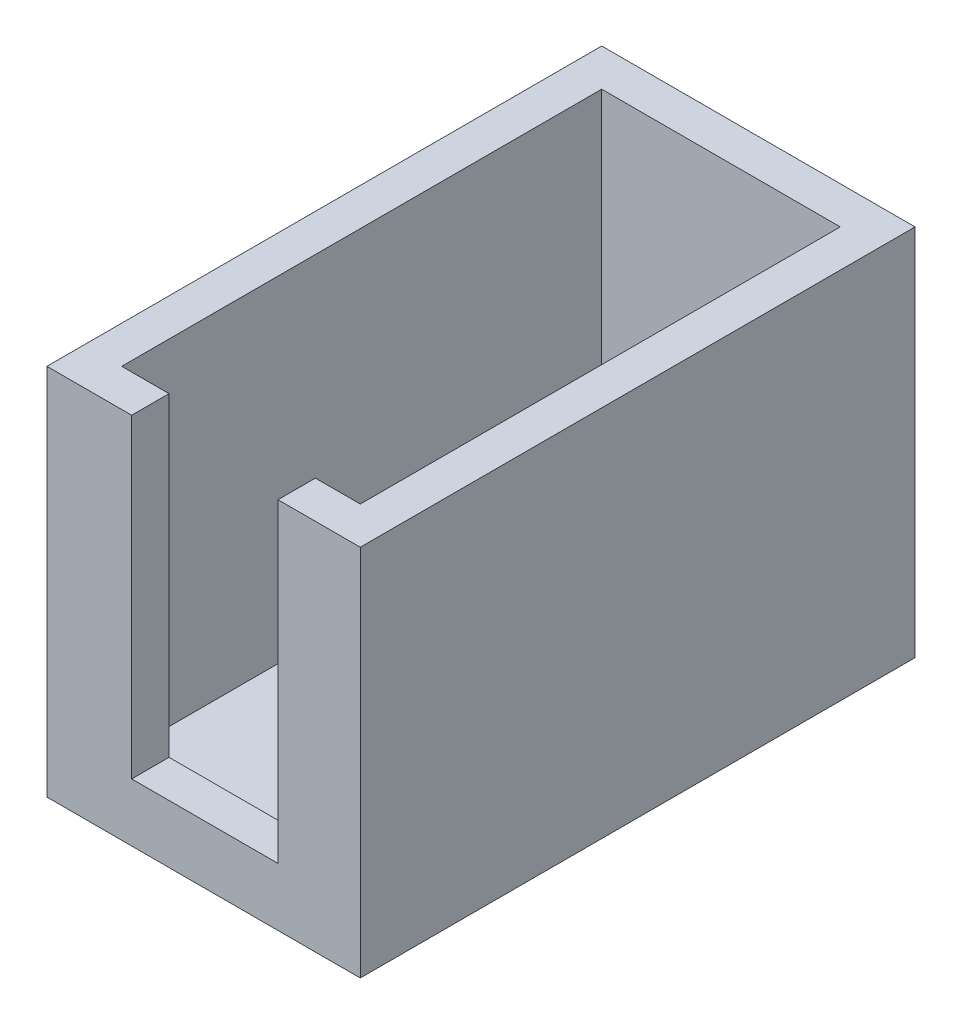
SolidWorks part; units mm, degrees
ref_plane "Front Plane" through (0, 0, 0) normal (0, 0, 1) x (1, 0, 0)
ref_plane "Top Plane" through (0, 0, 0) normal (0, 1, 0) x (1, 0, 0)
ref_plane "Right Plane" through (0, 0, 0) normal (1, 0, 0) x (0, 0, -1)
sketch "Sketch2" plane through (0, 0, 0) normal (0, 1, 0) x (1, 0, 0)
  line L1 (-10.127, -20.377) -> (10.127, -20.377)
  line L2 (-10.127, -20.377) -> (-10.127, 20.377)
  line L3 (-10.127, 20.377) -> (10.127, 20.377)
  line L4 (10.127, -20.377) -> (10.127, 20.377)
  line L5 (-10.127, -20.377) -> (10.127, 20.377) construction
  line L6 (-10.127, 20.377) -> (10.127, -20.377) construction
  point P0 (0, 0)
  dimension "D1" = 40.754
  dimension "D2" = 20.254
extrude "Boss-Extrude1" add sketch "Sketch2" along normal blind 28.5
shell "Shell1" thickness 3.175
sketch "Sketch3" plane through (0, 0, 23.552) normal (0, 0, 1) x (1, 0, 0)
  line L0 (-13.302, 28.5) -> (13.302, 28.5) construction
  line L1 (-6.1079, 28.5) -> (6.3157, 28.5)
  line L2 (-6.1079, 28.5) -> (-6.1079, 1.758)
  line L3 (-6.1079, 1.758) -> (6.3157, 1.758)
  line L4 (6.3157, 28.5) -> (6.3157, 1.758)
  line L5 (0, 0) -> (0.1039, 28.5) construction
extrude "Cut-Extrude1" cut sketch "Sketch3" against normal up to surface (3.175 mm away) up to face at (0, 14.25, 20.377)
